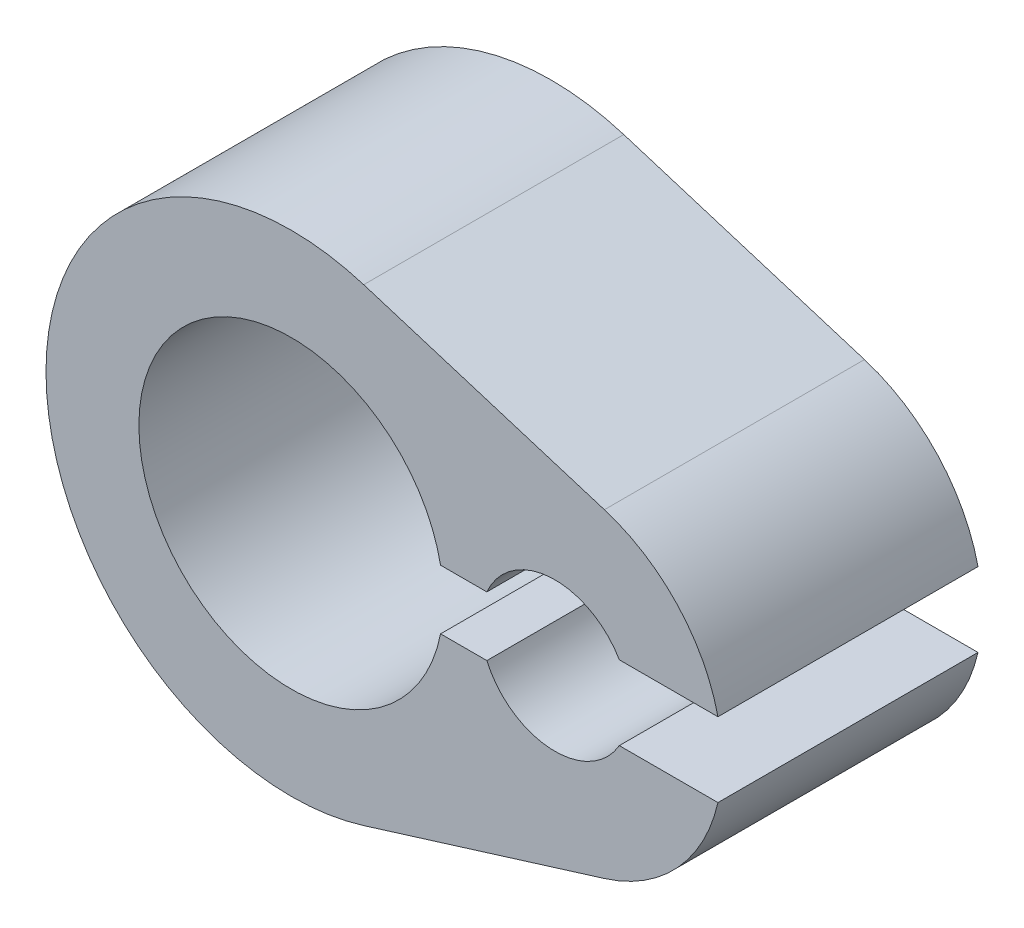
SolidWorks part; units mm, degrees
material "ABS"
ref_plane "Front Plane" through (0, 0, 0) normal (0, 0, 1) x (1, 0, 0)
ref_plane "Top Plane" through (0, 0, 0) normal (0, 1, 0) x (1, 0, 0)
ref_plane "Right Plane" through (0, 0, 0) normal (1, 0, 0) x (0, 0, -1)
sketch "Sketch1" plane through (0, 0, 0) normal (0, 0, 1) x (1, 0, 0)
  line L0 (1.9521, 6.3047) -> (8.431, 4.2987)
  line L1 (8.431, -4.2987) -> (1.9521, -6.3047)
  line L2 (4.0212, 0.8) -> (5.267, 0.8)
  line L3 (8.8321, 1) -> (11.4875, 1)
  line L4 (4.0212, -0.8) -> (5.267, -0.8)
  line L5 (11.4875, -1) -> (8.8321, -1)
  arc A0 (1.9521, 6.3047) -> (1.9521, -6.3047) centre (0, 0) ccw
  arc A1 (8.431, -4.2987) -> (11.4875, -1) centre (7.1, 0) ccw
  arc A2 (4.0212, 0.8) -> (4.0212, -0.8) centre (0, 0) ccw
  arc A3 (5.267, -0.8) -> (8.8321, -1) centre (7.1, 0) ccw
  arc A4 (8.8321, 1) -> (5.267, 0.8) centre (7.1, 0) ccw
  arc A5 (11.4875, 1) -> (8.431, 4.2987) centre (7.1, 0) ccw
  dimension "D1" = 13.2
  dimension "D2" = 9
  dimension "D3" = 7.1
  dimension "D4" = 2
  dimension "D5" = 4.1
  dimension "D6" = 1.6
  dimension "D7" = 2
extrude "Boss-Extrude1" add sketch "Sketch1" along normal blind 7
